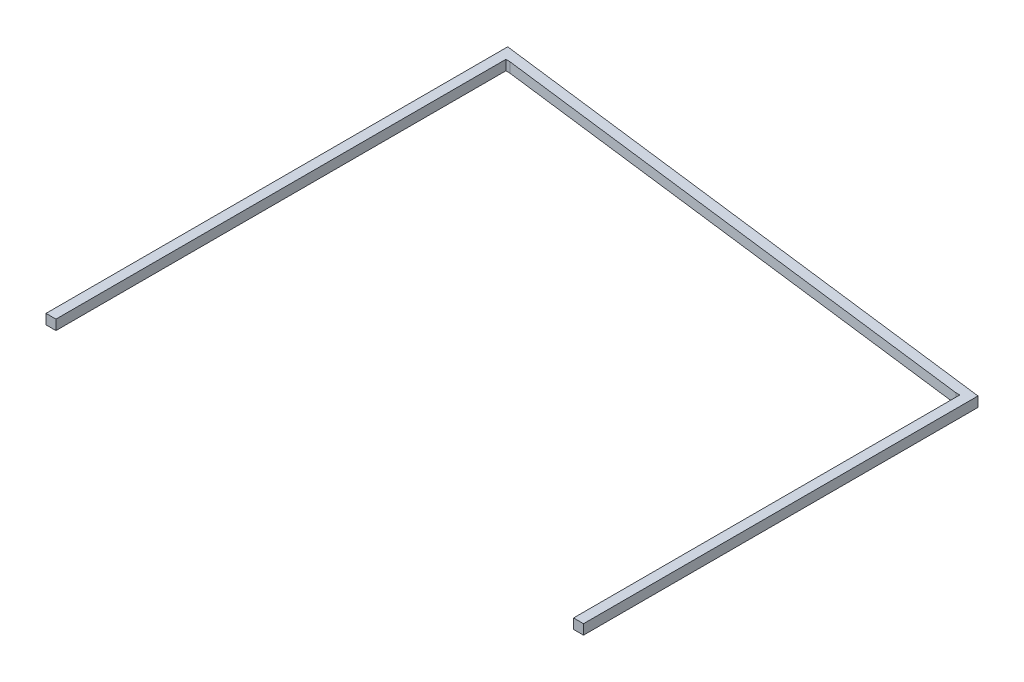
SolidWorks part; units mm, degrees
ref_plane "Front Plane" through (0, 0, 0) normal (0, 0, 1) x (1, 0, 0)
ref_plane "Top Plane" through (0, 0, 0) normal (0, 1, 0) x (1, 0, 0)
ref_plane "Right Plane" through (0, 0, 0) normal (1, 0, 0) x (0, 0, -1)
sketch "Sketch2" plane through (0, 0, 0) normal (0, 1, 0) x (1, 0, 0)
  line L0 (0, 0) -> (0, 358.775)
  line L1 (0, 358.775) -> (3.175, 358.775)
  line L2 (3.175, 358.775) -> (409.575, 307.975)
  line L3 (409.575, 307.975) -> (412.75, 307.975)
  line L4 (412.75, 307.975) -> (412.75, 0)
  line L5 (412.75, 0) -> (0, 0)
  line L6 (0, 0) -> (-7.9375, 0)
  line L7 (-7.9375, 0) -> (-7.9375, 368.1633)
  line L8 (-7.9375, 368.1633) -> (420.6875, 314.5852)
  line L9 (420.6875, 314.5852) -> (420.6875, 0)
  line L10 (420.6875, 0) -> (412.75, 0)
  dimension "D1" = 358.775
  dimension "D2" = 3.175
  dimension "D3" = 3.175
  dimension "D4" = 307.975
  dimension "D5" = 412.75
  dimension "D6" = 7.9375
  dimension "D7" = 7.9375
  dimension "D8" = 7.9375
extrude "Boss-Extrude1" add sketch "Sketch2" along normal blind 7.9375 contours L10 L9 L8 L7 L6 L0 L1 L2 L3 L4
